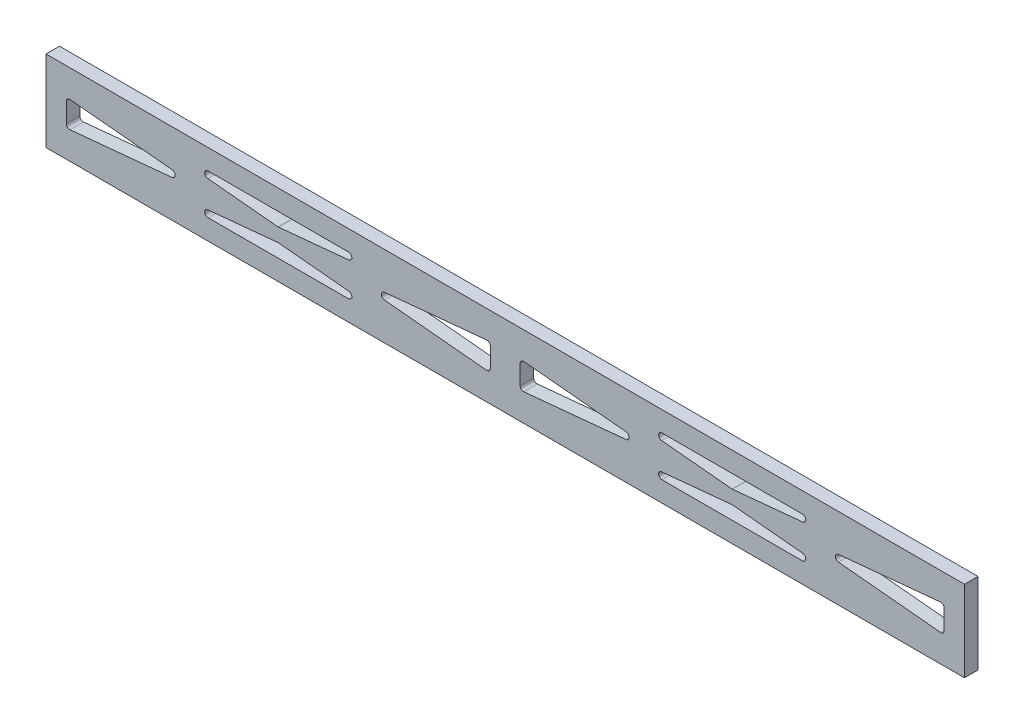
SolidWorks part; units mm, degrees
ref_plane "Front Plane" through (0, 0, 0) normal (0, 0, 1) x (1, 0, 0)
ref_plane "Top Plane" through (0, 0, 0) normal (0, 1, 0) x (1, 0, 0)
ref_plane "Right Plane" through (0, 0, 0) normal (1, 0, 0) x (0, 0, -1)
sketch "Sketch1" plane through (0, 0, 0) normal (0, 0, 1) x (1, 0, 0)
  line L1 (0, 0) -> (431.8, 0)
  line L2 (0, 0) -> (0, 38.1)
  line L3 (0, 38.1) -> (431.8, 38.1)
  line L4 (431.8, 0) -> (431.8, 38.1)
  dimension "D1" = 38.1
  dimension "D2" = 431.8
extrude "Boss-Extrude1" add sketch "Sketch1" along normal blind 6.35
sketch "Sketch3" plane through (0, 0, 6.35) normal (0, 0, 1) x (1, 0, 0)
  line L0 (9.525, 28.575) -> (208.8859, 9.525) construction
  line L1 (9.827, 31.7356) -> (209.1879, 12.6856)
  line L2 (9.223, 25.4144) -> (208.5839, 6.3644)
  line L3 (9.525, 9.525) -> (208.8859, 28.575) construction
  line L4 (215.9, 38.1) -> (215.9, 0) construction
  line L5 (431.8, 38.1) -> (0, 38.1) construction
  line L6 (0, 0) -> (431.8, 0) construction
  line L7 (222.9141, 38.1) -> (222.9141, 0)
  line L8 (9.525, 28.575) -> (9.525, 9.525)
  line L9 (9.525, 9.525) -> (422.275, 9.525)
  line L10 (422.275, 9.525) -> (422.275, 28.575)
  line L11 (422.275, 28.575) -> (9.525, 28.575)
  line L12 (9.525, 28.575) -> (9.525, 9.525)
  line L13 (9.525, 9.525) -> (422.275, 9.525)
  line L14 (422.275, 9.525) -> (422.275, 28.575)
  line L15 (422.275, 28.575) -> (9.525, 28.575)
  line L16 (208.8859, 38.1) -> (208.8859, 0)
  line L17 (9.223, 12.6856) -> (208.5839, 31.7356)
  line L18 (9.827, 6.3644) -> (209.1879, 25.4144)
  line L19 (215.9, 38.1) -> (215.9, 0) construction
  line L20 (215.9, 70.4248) -> (215.9, 0) construction
  line L21 (422.275, 9.525) -> (222.9141, 28.575) construction
  line L22 (422.577, 12.6856) -> (223.2161, 31.7356)
  line L23 (421.973, 6.3644) -> (222.6121, 25.4144)
  line L24 (422.275, 28.575) -> (222.9141, 9.525) construction
  line L25 (421.973, 31.7356) -> (222.6121, 12.6856)
  line L26 (422.577, 25.4144) -> (223.2161, 6.3644)
  arc A0 (222.9141, 38.1) -> (208.8859, 38.1) centre (215.9, 38.1) ccw
  arc A1 (208.8859, 0) -> (222.9141, 0) centre (215.9, 0) ccw
  arc A2 (9.827, 31.7356) -> (9.223, 25.4144) centre (9.525, 28.575) ccw
  arc A3 (208.5839, 6.3644) -> (209.1879, 12.6856) centre (208.8859, 9.525) ccw
  arc A4 (9.223, 12.6856) -> (9.827, 6.3644) centre (9.525, 9.525) ccw
  arc A5 (209.1879, 25.4144) -> (208.5839, 31.7356) centre (208.8859, 28.575) ccw
  arc A6 (422.577, 12.6856) -> (421.973, 6.3644) centre (422.275, 9.525) cw
  arc A7 (222.6121, 25.4144) -> (223.2161, 31.7356) centre (222.9141, 28.575) cw
  arc A8 (421.973, 31.7356) -> (422.577, 25.4144) centre (422.275, 28.575) cw
  arc A9 (223.2161, 6.3644) -> (222.6121, 12.6856) centre (222.9141, 9.525) cw
  point P7 (215.9, 19.05)
  point P16 (109.2055, 19.05)
  point P22 (109.2055, 19.05)
  point P33 (322.5945, 19.05)
  point P40 (322.5945, 19.05)
  point P45 (0, 0)
  dimension "D2" = 7.0141
  dimension "D3" = 3.175
  dimension "D1" = 9.525
extrude "Cut-Extrude1" cut sketch "Sketch3" against normal through all contours L12 L17 L2 | L1 L17 L15 | L18 L13 L2 | L18 L1 L16 | L25 L23 L7 | L25 L15 L22 | L23 L26 L13 | L14 L26 L22
fillet "Fillet1" radius 1.5875 24 edges at (175.5078, 9.525, 3.175) (42.9032, 9.525, 3.175) (109.2055, 15.8605, 3.175) (208.8859, 12.7145, 3.175) (142.5836, 19.05, 3.175) (208.8859, 25.3855, 3.175) (222.9141, 25.3855, 3.175) (289.2164, 19.05, 3.175) (222.9141, 12.7145, 3.175) (256.2922, 28.575, 3.175) (388.8968, 28.575, 3.175) (322.5945, 22.2395, 3.175) (422.275, 12.7145, 3.175) (355.9727, 19.05, 3.175) (422.275, 25.3855, 3.175) (388.8968, 9.525, 3.175) (256.2922, 9.525, 3.175) (322.5945, 15.8605, 3.175) (42.9032, 28.575, 3.175) (175.5078, 28.575, 3.175) (109.2055, 22.2395, 3.175) (9.525, 25.3855, 3.175) (75.8273, 19.05, 3.175) (9.525, 12.7145, 3.175)
move or copy body "Body-Move/Copy1" [suppressed] bodies to move or copy 101 parameters "D1"=0, "D2"=0, "D3"=0
